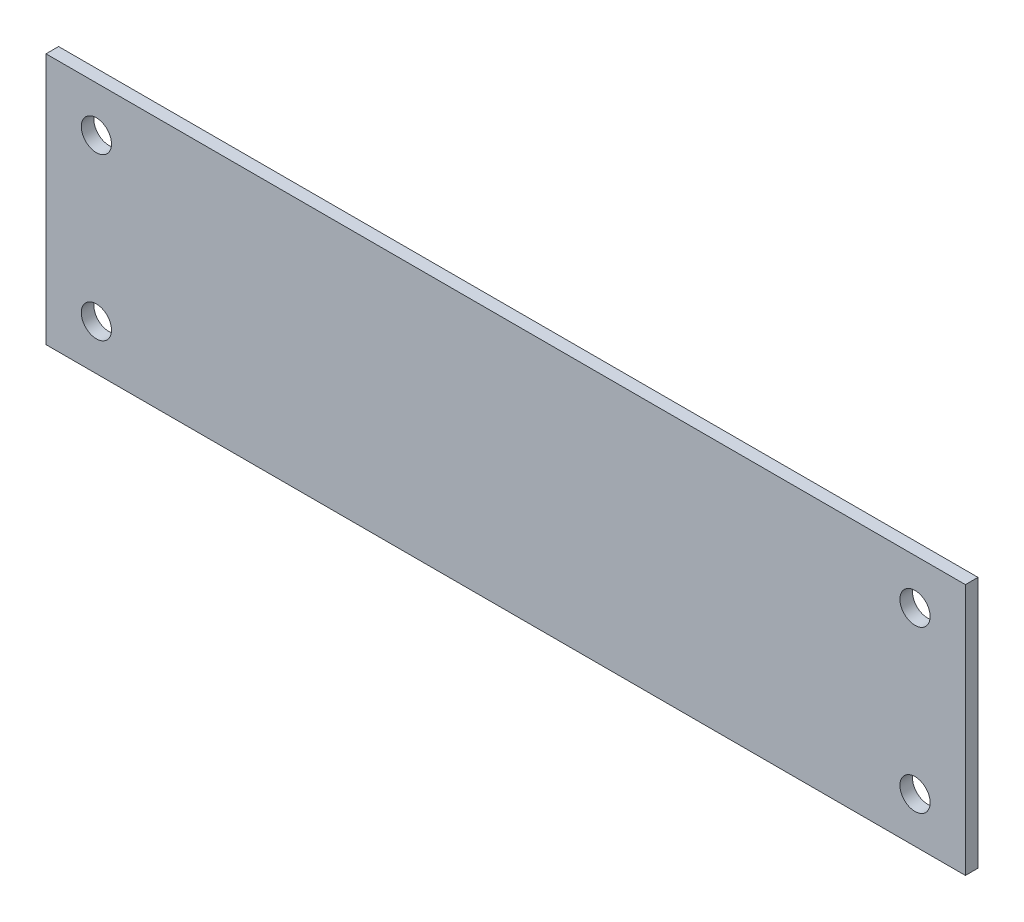
SolidWorks part; units mm, degrees
ref_plane "Front Plane" through (0, 0, 0) normal (0, 0, 1) x (1, 0, 0)
ref_plane "Top Plane" through (0, 0, 0) normal (0, 1, 0) x (1, 0, 0)
ref_plane "Right Plane" through (0, 0, 0) normal (1, 0, 0) x (0, 0, -1)
sketch "Sketch1" plane through (0, 0, 0) normal (0, 0, 1) x (1, 0, 0)
  line L1 (-182.5, 50) -> (182.5, 50)
  line L2 (-182.5, 50) -> (-182.5, -50)
  line L3 (-182.5, -50) -> (182.5, -50)
  line L4 (182.5, 50) -> (182.5, -50)
  line L5 (-182.5, 50) -> (182.5, -50) construction
  line L6 (-182.5, -50) -> (182.5, 50) construction
  circle A0 centre (162.5, 32) radius 6
  circle A1 centre (162.5, -32) radius 6
  circle A2 centre (-162.5, 32) radius 6
  circle A3 centre (-162.5, -32) radius 6
  point P0 (0, 0)
  dimension "D3" = 18
  dimension "D4" = 18
  dimension "D5" = 12
  dimension "D6" = 12
  dimension "D7" = 12
  dimension "D8" = 12
  dimension "D9" = 20
  dimension "D10" = 20
  dimension "D11" = 20
  dimension "D12" = 20
  dimension "D13" = 18
  dimension "D14" = 18
  dimension "D1" = 365
  dimension "D2" = 100
extrude "Boss-Extrude1" add sketch "Sketch1" along normal blind 5
